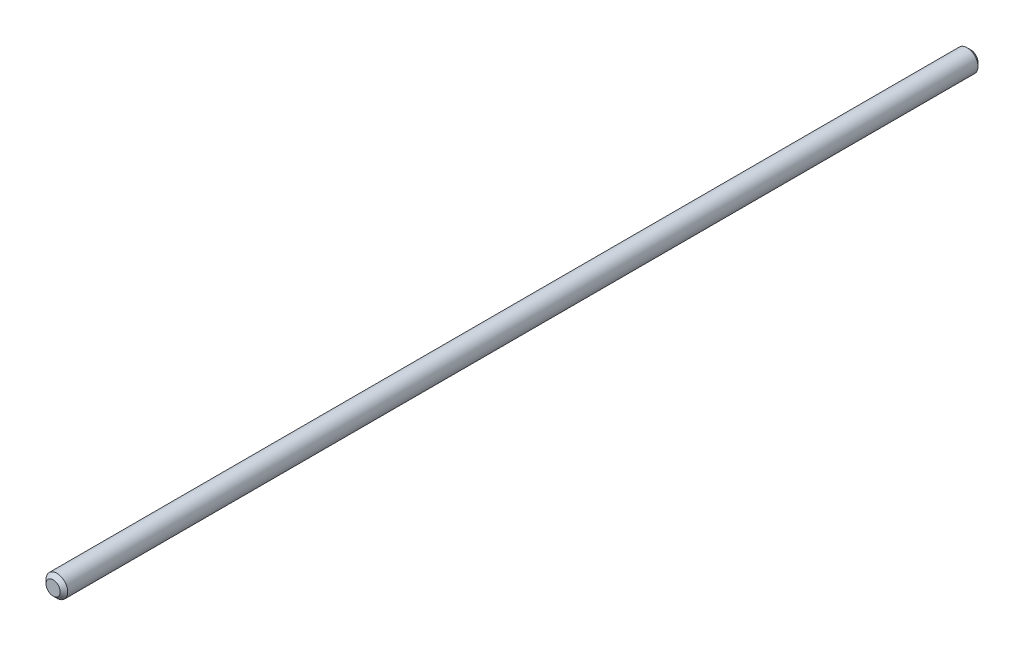
SolidWorks part; units mm, degrees
ref_plane "Спереди" through (0, 0, 0) normal (0, 0, 1) x (1, 0, 0)
ref_plane "Сверху" through (0, 0, 0) normal (0, 1, 0) x (1, 0, 0)
ref_plane "Справа" through (0, 0, 0) normal (1, 0, 0) x (0, 0, -1)
sketch "Эскиз1" plane through (0, 0, 0) normal (0, 0, 1) x (1, 0, 0)
  circle A0 centre (0, 0) radius 2.9
extrude "Бобышка-Вытянуть1" add sketch "Эскиз1" along normal blind 245 contours A0
chamfer "Фаска1" distance 1 angle 45 2 edges at (2.9, 0, 0) (2.9, 0, 245)
